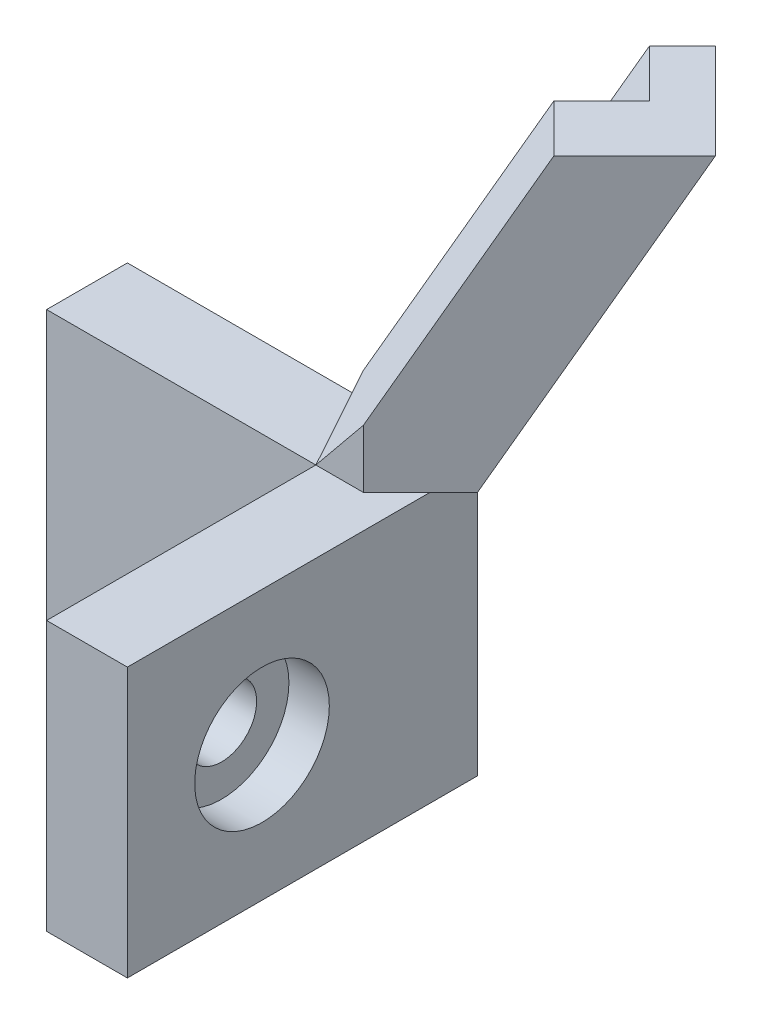
SolidWorks part; units mm, degrees
ref_plane "前视基准面" through (0, 0, 0) normal (0, 0, 1) x (1, 0, 0)
ref_plane "上视基准面" through (0, 0, 0) normal (0, 1, 0) x (1, 0, 0)
ref_plane "右视基准面" through (0, 0, 0) normal (1, 0, 0) x (0, 0, -1)
other "Configuration Table"
sketch "草图1" plane through (0, 0, 0) normal (0, 1, 0) x (1, 0, 0)
  line L0 (0, 0) -> (0, -20)
  line L1 (0, 0) -> (-20, 0)
  line L2 (-20, 0) -> (-20, 6)
  line L3 (0, -20) -> (6, -20)
  line L4 (-20, 6) -> (6, 6)
  line L5 (6, 6) -> (6, -20)
extrude "凸台-拉伸2" add sketch "草图1" along normal blind 20
sketch "草图2" plane through (6, 0, 0) normal (1, 0, 0) x (0, 0, -1)
  line L0 (-20, 20) -> (6, 20) construction
  line L1 (-20, 0) -> (0, 0)
  line L2 (-20, 0) -> (-20, 20)
  line L3 (-20, 20) -> (0, 20)
  line L4 (0, 0) -> (0, 20)
  line L5 (-20, 20) -> (0, 0)
  circle A0 centre (-10, 10) radius 2.6
extrude "切除-拉伸1" cut sketch "草图2" against normal blind 20 contours L5 A0 | L5 A0
sketch "草图3" plane through (6, 0, 0) normal (1, 0, 0) x (0, 0, -1)
  circle A0 centre (-10, 10) radius 5
extrude "切除-拉伸2" cut sketch "草图3" against normal blind 3
sketch "草图4" plane through (0, 20, 0) normal (0, 1, 0) x (1, 0, 0)
  line L0 (6, 6) -> (65.397, 65.397)
  line L1 (6, 6) -> (12, 0)
  line L2 (6, 6) -> (0, 12)
  line L3 (12, 0) -> (0, 0)
  line L4 (0, 0) -> (0, 12)
  line L5 (65.397, 65.397) -> (67.1647, 63.6292)
  line L6 (65.397, 65.397) -> (63.6292, 67.1647)
  line L7 (67.1647, 63.6292) -> (7.7678, 4.2322)
  line L8 (63.6292, 67.1647) -> (4.2322, 7.7678)
  line L9 (4.2322, 7.7678) -> (7.7678, 4.2322)
  line M14 (6, -20) -> (6, 6)
  line M15 (6, 6) -> (-20, 6)
extrude "凸台-拉伸3" add sketch "草图4" along normal blind 84 contours L7 L5 L0 L1 | L6 L8 L2 L0 | L4 L2 M15 | L4 L3 M14 M15 | L3 L1 M14
sketch "草图5" plane through (-1.7678, 0, -1.7678) normal (-0.7071, 0, -0.7071) x (-0.7071, 0, 0.7071)
  line L1 (-92.4853, 104) -> (-92.4853, 20)
  line L2 (-92.4853, 20) -> (-8.4853, 20)
  line L4 (-8.4853, 20) -> (-20.9853, 41.6506)
  line L6 (0, 20) -> (-12.5, 41.6506)
  line L7 (-20.9853, 41.6506) -> (-12.5, 41.6506)
  line L8 (-8.4853, 20) -> (-92.4853, 20)
  line L9 (-92.4853, 104) -> (0, 104)
  line L10 (0, 104) -> (0, 20)
  line L11 (-92.4853, 20) -> (-8.4853, 20)
  line M4 (-92.4853, 20) -> (-8.4853, 20)
  line M5 (-8.4853, 20) -> (-8.4853, 104)
  line M6 (-8.4853, 104) -> (-92.4853, 104)
  line M7 (-92.4853, 104) -> (-92.4853, 20)
extrude "切除-拉伸3" cut sketch "草图5" against normal blind 84 contours L4 L7 L6 M5 M6 M7 M4 | L10 L9 L6 M5
sketch "草图6" plane through (1.7678, 0, 1.7678) normal (0.7071, 0, 0.7071) x (0.7071, 0, -0.7071)
  line L0 (8.4853, 34.6969) -> (8.4853, 20)
  line L1 (8.4853, 20) -> (0, 20)
  line L2 (0, 20) -> (8.4853, 34.6969)
extrude "切除-拉伸4" cut sketch "草图6" along normal blind 84
sketch "草图7" plane through (-1.7678, 0, -1.7678) normal (-0.7071, 0, -0.7071) x (-0.7071, 0, 0.7071)
  line L0 (-2.5, 20) -> (0, 20)
  line L1 (-8.4853, 20) -> (-2.5, 20)
  line L2 (-8.4853, 20) -> (-8.4853, 104)
  line L3 (-8.4853, 104) -> (-2.5, 104)
  line L4 (-2.5, 20) -> (-2.5, 104)
  line L5 (0, 20) -> (-2.5, 24.3301)
  line L6 (-2.5, 24.3301) -> (-2.5, 20)
  line M7 (-8.4853, 20) -> (-8.4853, 34.6969)
extrude "切除-拉伸5" cut sketch "草图7" along normal blind 84 contours L1 L4 L3 L2 M7 | L0 L5 L4
sketch "草图9" plane through (-1.6237, 1.3258, 1.6237) normal (0.6124, -0.5, -0.6124) x (-0.4743, 0.3873, -0.7906)
  line L0 (18.5876, 42.7654) -> (23.0597, 40.5293)
  line L1 (23.0597, 40.5293) -> (27.5319, 38.2932)
  line L2 (27.5319, 38.2932) -> (18.5876, 20.4047)
  line L4 (11.8794, 18.1686) -> (23.0597, 40.5293)
  line L5 (18.5876, 20.4047) -> (14.1155, 22.6408)
  line L6 (14.1155, 22.6408) -> (23.0597, 40.5293)
  line L7 (25.2958, 39.4113) -> (20.8237, 30.467)
  circle A0 centre (20.8237, 30.467) radius 1.5
extrude "凸台-拉伸4" add sketch "草图9" against normal blind 3
sketch "草图10" plane through (-1.7678, 0, -1.7678) normal (0.7071, 0, 0.7071) x (0.7071, 0, -0.7071)
  line L0 (17.5212, 41.6506) -> (20.9853, 41.6506)
  line L1 (20.9853, 41.6506) -> (18.3872, 43.1506)
  line L2 (18.3872, 43.1506) -> (17.5212, 41.6506)
extrude "切除-拉伸6" cut sketch "草图10" against normal blind 6
sketch "草图11" plane through (-1.7678, 0, -1.7678) normal (-0.7071, 0, -0.7071) x (-0.7071, 0, 0.7071)
  line L0 (-8.3872, 25.8301) -> (-5.0212, 20)
  line L1 (-5.9853, 20) -> (9.8995, 20) construction
  line L2 (-5.0212, 20) -> (-8.4853, 20)
  line L3 (-8.4853, 20) -> (-10.9853, 24.3301)
  line L4 (-10.9853, 24.3301) -> (-8.3872, 25.8301)
extrude "切除-拉伸7" cut sketch "草图11" against normal blind 2.5
